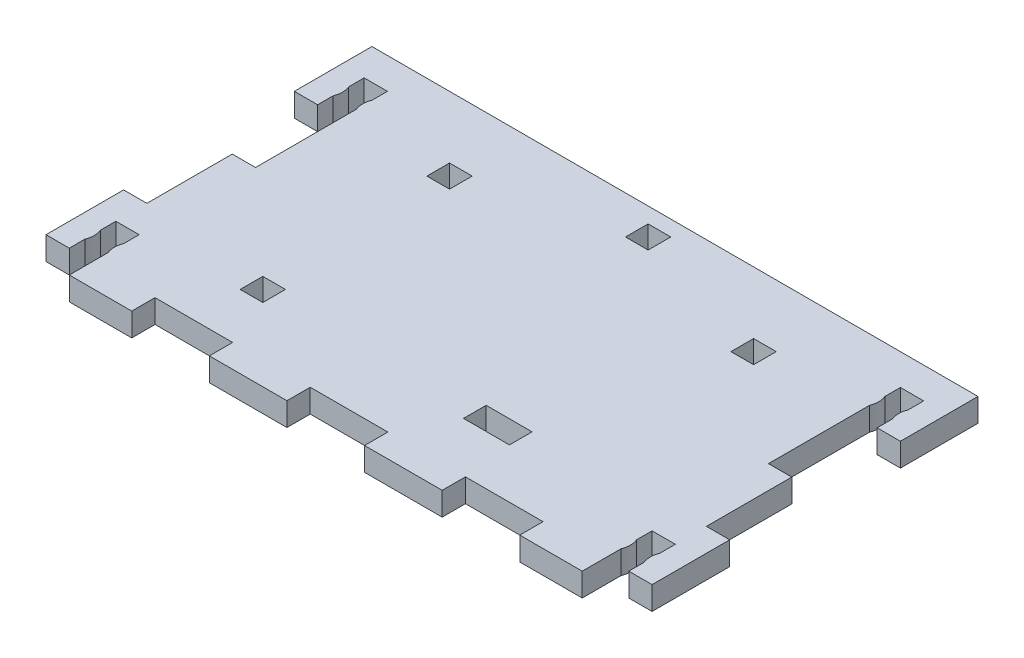
SolidWorks part; units mm, degrees
ref_plane "Front Plane" through (0, 0, 0) normal (0, 0, 1) x (1, 0, 0)
ref_plane "Top Plane" through (0, 0, 0) normal (0, 1, 0) x (1, 0, 0)
ref_plane "Right Plane" through (0, 0, 0) normal (1, 0, 0) x (0, 0, -1)
sketch "Sketch1" plane through (0, 0, 0) normal (0, 1, 0) x (1, 0, 0)
  line L0 (1.5603, 19.8766) -> (1.5603, -31.5242) construction
  line L1 (-31.4897, 19.8766) -> (34.6103, 19.8766)
  line L2 (-31.4897, 15.8766) -> (-31.4897, 13.8766)
  line L3 (-31.4897, -22.1234) -> (34.6103, -22.1234)
  line L4 (34.6103, 15.8766) -> (34.6103, 13.8766)
  line L5 (34.6103, 19.8766) -> (40.6103, 19.8766)
  line L6 (40.6103, 19.8766) -> (40.6103, 9.8766)
  line L7 (40.6103, 9.8766) -> (37.6103, 9.8766)
  line L8 (37.6103, 9.8766) -> (37.6103, 11.8766)
  line L9 (37.6103, 15.8766) -> (34.6103, 15.8766)
  line L10 (34.6103, -16.1234) -> (37.6103, -16.1234)
  line L11 (37.6103, -16.1234) -> (37.6103, -18.1234)
  line L12 (37.6103, -22.1234) -> (40.6103, -22.1234)
  line L13 (40.6103, -22.1234) -> (40.6103, -12.1234)
  line L14 (40.6103, -12.1234) -> (37.6103, -12.1234)
  line L15 (37.6103, -12.1234) -> (37.6103, -1.1234)
  line L16 (37.6103, -1.1234) -> (34.6103, -1.1234)
  line L17 (34.6103, -22.1234) -> (34.6103, -25.1234)
  line L18 (34.6103, -25.1234) -> (26.5603, -25.1234)
  line L19 (26.5603, -25.1234) -> (26.5603, -22.1234)
  line L20 (16.5603, -22.1234) -> (16.5603, -25.1234)
  line L21 (16.5603, -25.1234) -> (6.5603, -25.1234)
  line L22 (6.5603, -25.1234) -> (6.5603, -22.1234)
  line L23 (-31.4897, -22.1234) -> (-31.4897, -25.1234)
  line L24 (-3.4397, -25.1234) -> (-3.4397, -22.1234)
  line L25 (-13.4397, -25.1234) -> (-3.4397, -25.1234)
  line L26 (-13.4397, -22.1234) -> (-13.4397, -25.1234)
  line L27 (-23.4397, -25.1234) -> (-23.4397, -22.1234)
  line L28 (-31.4897, -25.1234) -> (-23.4397, -25.1234)
  line L29 (-34.4897, -1.1234) -> (-31.4897, -1.1234)
  line L30 (-34.4897, -12.1234) -> (-34.4897, -1.1234)
  line L31 (-37.4897, -12.1234) -> (-34.4897, -12.1234)
  line L32 (-37.4897, -22.1234) -> (-37.4897, -12.1234)
  line L33 (-34.4897, -22.1234) -> (-37.4897, -22.1234)
  line L34 (-34.4897, -16.1234) -> (-34.4897, -18.1234)
  line L35 (-31.4897, -16.1234) -> (-34.4897, -16.1234)
  line L36 (-34.4897, 15.8766) -> (-31.4897, 15.8766)
  line L37 (-34.4897, 9.8766) -> (-34.4897, 11.8766)
  line L38 (-37.4897, 9.8766) -> (-34.4897, 9.8766)
  line L39 (-37.4897, 19.8766) -> (-37.4897, 9.8766)
  line L40 (-31.4897, 19.8766) -> (-37.4897, 19.8766)
  line L41 (-19.4897, 11.8766) -> (-19.4897, 8.9566)
  line L42 (19.6903, 11.8766) -> (22.6103, 11.8766)
  line L43 (19.6903, 11.8766) -> (19.6903, 8.9566)
  line L44 (19.6903, 8.9566) -> (22.6103, 8.9566)
  line L45 (22.6103, 11.8766) -> (22.6103, 8.9566)
  line L46 (-16.5697, 8.9566) -> (-19.4897, 8.9566)
  line L47 (-16.5697, 11.8766) -> (-16.5697, 8.9566)
  line L48 (-16.5697, 11.8766) -> (-19.4897, 11.8766)
  line L49 (0.1003, 17.8766) -> (3.0203, 17.8766)
  line L50 (3.0203, 17.8766) -> (3.0203, 14.9566)
  line L51 (3.0203, 14.9566) -> (0.1003, 14.9566)
  line L52 (0.1003, 17.8766) -> (0.1003, 14.9566)
  line L53 (37.6103, 13.8766) -> (37.6103, 15.8766)
  line L54 (37.6103, -20.1234) -> (37.6103, -22.1234)
  line L55 (34.6103, -20.1234) -> (34.6103, -22.1234)
  line L56 (36.1103, -16.1234) -> (36.1103, -22.1234) construction
  line L57 (-34.4897, -20.1234) -> (-34.4897, -22.1234)
  line L58 (-31.4897, -20.1234) -> (-31.4897, -22.1234)
  line L59 (-31.4897, 11.8766) -> (-31.4897, -1.1234)
  line L60 (9.9103, -12.8034) -> (15.8303, -12.8034)
  line L61 (9.9103, -12.8034) -> (9.9103, -15.7234)
  line L62 (9.9103, -15.7234) -> (15.8303, -15.7234)
  line L63 (15.8303, -12.8034) -> (15.8303, -15.7234)
  line L64 (-18.8697, -12.8034) -> (-15.9497, -12.8034)
  line L65 (-18.8697, -12.8034) -> (-18.8697, -15.7234)
  line L66 (-18.8697, -15.7234) -> (-15.9497, -15.7234)
  line L67 (-15.9497, -12.8034) -> (-15.9497, -15.7234)
  line L68 (-34.4897, 13.8766) -> (-34.4897, 15.8766)
  line L69 (-31.4897, -16.1234) -> (-31.4897, -18.1234)
  line L70 (34.6103, 11.8766) -> (34.6103, -18.1234)
  arc A0 (37.6103, -20.1234) -> (37.6103, -18.1234) centre (40.0103, -19.1234) cw
  arc A1 (34.6103, -20.1234) -> (34.6103, -18.1234) centre (32.2103, -19.1234) ccw
  arc A2 (37.6103, 11.8766) -> (37.6103, 13.8766) centre (40.0103, 12.8766) cw
  arc A3 (34.6103, 11.8766) -> (34.6103, 13.8766) centre (32.2103, 12.8766) ccw
  arc A4 (-34.4897, -20.1234) -> (-34.4897, -18.1234) centre (-36.8897, -19.1234) ccw
  arc A5 (-31.4897, -20.1234) -> (-31.4897, -18.1234) centre (-29.0897, -19.1234) cw
  arc A6 (-31.4897, 11.8766) -> (-31.4897, 13.8766) centre (-29.0897, 12.8766) cw
  arc A7 (-34.4897, 11.8766) -> (-34.4897, 13.8766) centre (-36.8897, 12.8766) ccw
  point P59 (1.5603, 17.8766)
  point P60 (1.5603, 14.9566)
  point P94 (-23.2044, 16.2752)
  dimension "D1" = 66.1
  dimension "D2" = 42
  dimension "D3" = 6
  dimension "D4" = 10
  dimension "D5" = 3
  dimension "D6" = 6
  dimension "D7" = 3
  dimension "D8" = 3
  dimension "D9" = 6
  dimension "D10" = 0
  dimension "D11" = 3
  dimension "D12" = 10
  dimension "D13" = 3
  dimension "D14" = 11
  dimension "D15" = 3
  dimension "D16" = 17
  dimension "D17" = 3
  dimension "D18" = 8.05
  dimension "D19" = 10
  dimension "D20" = 3
  dimension "D21" = 10
  dimension "D22" = 2.92
  dimension "D23" = 2.92
  dimension "D24" = 8
  dimension "D25" = 12
  dimension "D26" = 1.46
  dimension "D27" = 2.92
  dimension "D28" = 2
  dimension "D29" = 3.08
  dimension "D30" = 5.92
  dimension "D31" = 2.92
  dimension "D32" = 2.92
  dimension "D33" = 2.92
  dimension "D34" = 6.4
  dimension "D35" = 6.4
  dimension "D36" = 25.86
  dimension "D37" = 18.78
  dimension "D38" = 12.62
extrude "Boss-Extrude1" add sketch "Sketch1" along normal blind 3 contours L0 L1 L2 L3 L48 L47 L46 L41 | L1 L0 L3 L4 L42 L45 L44 L43 | L15 L16 L4 L10 L11 L12 L13 L14 | L9 L8 L7 L6 L5 L4 | L19 L18 L17 L3 | L22 L21 L20 L3 | L3 L26 L25 L24 | L23 L28 L27 L3 | L35 L2 L29 L30 L31 L32 L33 L34 | L2 L40 L39 L38 L37 L36
